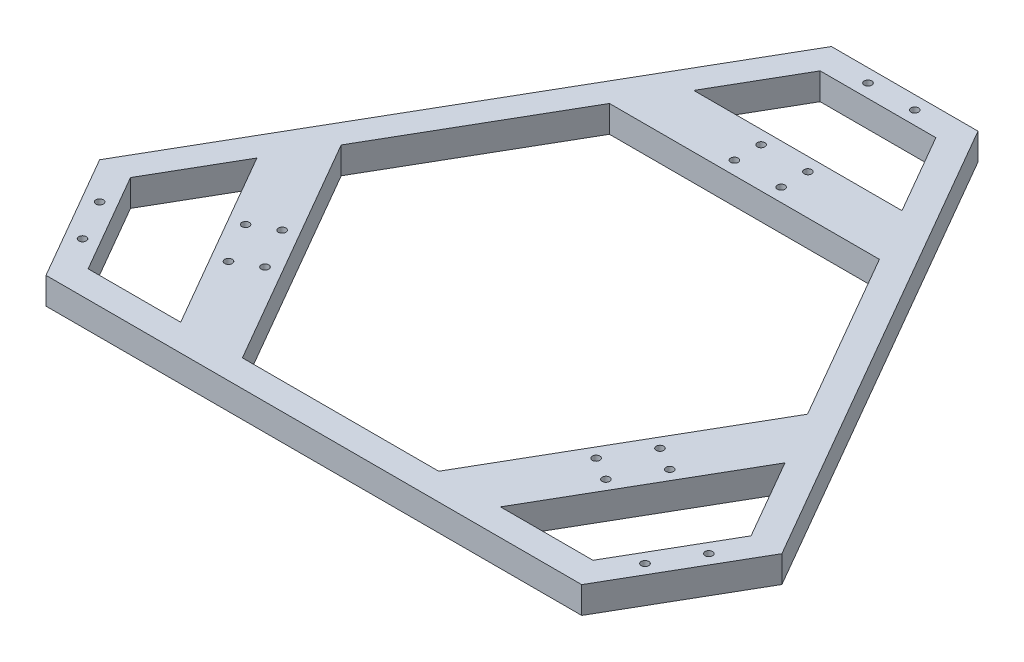
SolidWorks part; units mm, degrees
ref_plane "Front Plane" through (0, 0, 0) normal (0, 0, 1) x (1, 0, 0)
ref_plane "Top Plane" through (0, 0, 0) normal (0, 1, 0) x (1, 0, 0)
ref_plane "Right Plane" through (0, 0, 0) normal (1, 0, 0) x (0, 0, -1)
sketch "Sketch1" plane through (0, 0, 0) normal (0, 1, 0) x (1, 0, 0)
  line L0 (-55, 308.8818) -> (55, 308.8818)
  line L1 (55, 308.8818) -> (294.9995, -106.8095)
  line L2 (294.9995, -106.8095) -> (239.9995, -202.0723)
  line L3 (239.9995, -202.0723) -> (-239.9995, -202.0723)
  line L4 (-239.9995, -202.0723) -> (-294.9995, -106.8095)
  line L5 (-294.9995, -106.8095) -> (-55, 308.8818)
  line L6 (-254.6642, -227.4723) -> (254.6642, -227.4723)
  line L7 (254.6642, -227.4723) -> (324.3289, -106.8095)
  line L8 (324.3289, -106.8095) -> (69.6647, 334.2818)
  line L9 (69.6647, 334.2818) -> (-69.6647, 334.2818)
  line L10 (-69.6647, 334.2818) -> (-324.3289, -106.8095)
  line L11 (-324.3289, -106.8095) -> (-254.6642, -227.4723)
  line L12 (-251.0054, -30.6095) -> (-152.0113, -202.0723)
  line L13 (-152.0113, -202.0723) -> (-93.3526, -202.0723)
  line L14 (-93.3526, -202.0723) -> (-221.6761, 20.1905)
  line L15 (152.0113, -202.0723) -> (251.0054, -30.6095)
  line L16 (93.3526, -202.0723) -> (221.6761, 20.1905)
  line L17 (-98.9941, 232.6818) -> (98.9941, 232.6818)
  line L18 (-128.3235, 181.8818) -> (128.3235, 181.8818)
  circle A1 centre (0, 0) radius 313.7403 construction
  point P26 (0, 0)
  point P30 (0, 0)
  dimension "D1" = 110
  dimension "D2" = 110
  dimension "D3" = 110
  dimension "D4" = 479.999
  dimension "D5" = 479.999
  dimension "D6" = 479.999
  dimension "D7" = 25.4
  dimension "D8" = 25.4
  dimension "D9" = 25.4
  dimension "D10" = 25.4
  dimension "D11" = 25.4
  dimension "D12" = 25.4
  dimension "D13" = 50.8
  dimension "D14" = 76.2
  dimension "D15" = 76.2
  dimension "D16" = 50.8
  dimension "D17" = 76.2
  dimension "D18" = 50.8
extrude "Boss-Extrude2" add sketch "Sketch1" along normal blind 25.4 contours L3 L14 L5 L12 | L10 L11 L6 L7 L8 L9 L4 L5 L0 L1 L2 L3 | L16 L3 L15 L1 | L5 L18 L1 L17
sketch "Sketch2" plane through (0, 0, 0) normal (0, -1, 0) x (1, 0, 0)
  line L0 (-324.3289, 106.8095) -> (-254.6642, 227.4723) construction
  line L1 (-324.3289, 106.8095) -> (-289.6106, 141.5435) construction
  line L2 (-267.3856, 180.0383) -> (-254.6642, 227.4723) construction
  line L3 (-251.0054, 30.6095) -> (-152.0113, 202.0723) construction
  line L4 (-93.3526, 202.0723) -> (-221.6761, -20.1905) construction
  line L5 (-251.0054, 30.6095) -> (-201.6224, 90.7435) construction
  line L6 (-179.3974, 129.2383) -> (-152.0113, 202.0723) construction
  line L7 (-157.4003, 116.5383) -> (-152.0113, 202.0723) construction
  line L8 (-179.6253, 78.0435) -> (-251.0054, 30.6095) construction
  circle A0 centre (-289.6106, 141.5435) radius 3.5719
  circle A1 centre (-267.3856, 180.0383) radius 3.5719
  circle A2 centre (267.3856, 180.0383) radius 3.5719
  circle A3 centre (289.6106, 141.5435) radius 3.5719
  circle A4 centre (22.225, -321.5818) radius 3.5719
  circle A5 centre (-22.225, -321.5818) radius 3.5719
  circle A6 centre (-201.6224, 90.7435) radius 3.5719
  circle A9 centre (-179.3974, 129.2383) radius 3.5719
  circle A10 centre (-157.4003, 116.5383) radius 3.5719
  circle A11 centre (-179.6253, 78.0435) radius 3.5719
  circle A12 centre (201.6224, 90.7435) radius 3.5719
  circle A13 centre (179.3974, 129.2383) radius 3.5719
  circle A14 centre (-22.225, -219.9818) radius 3.5719
  circle A15 centre (22.225, -219.9818) radius 3.5719
  circle A16 centre (179.6253, 78.0435) radius 3.5719
  circle A17 centre (157.4003, 116.5383) radius 3.5719
  circle A18 centre (-22.225, -194.5818) radius 3.5719
  circle A19 centre (22.225, -194.5818) radius 3.5719
  dimension "D3" = 7.1437
  dimension "D4" = 7.1437
  dimension "D5" = 44.45
  dimension "D7" = 7.1437
  dimension "D8" = 7.1437
  dimension "D9" = 7.1437
  dimension "D10" = 7.1437
  dimension "D1" = 12.7
  dimension "D2" = 12.7
  dimension "D11" = 12.7
  dimension "D12" = 12.7
  dimension "D13" = 12.7
  dimension "D14" = 12.7
  dimension "D15" = 44.45
  dimension "D16" = 44.45
  dimension "D6" = 3
  dimension "D17" = 3
  dimension "D18" = 3
extrude "Cut-Extrude1" cut sketch "Sketch2" against normal blind 25.4 contours A1 | A0 | A9 | A6 | A10 | A11 | A17 | A16 | A12 | A13 | A2 | A3 | A18 | A19 | A15 | A14 | A5 | A4
